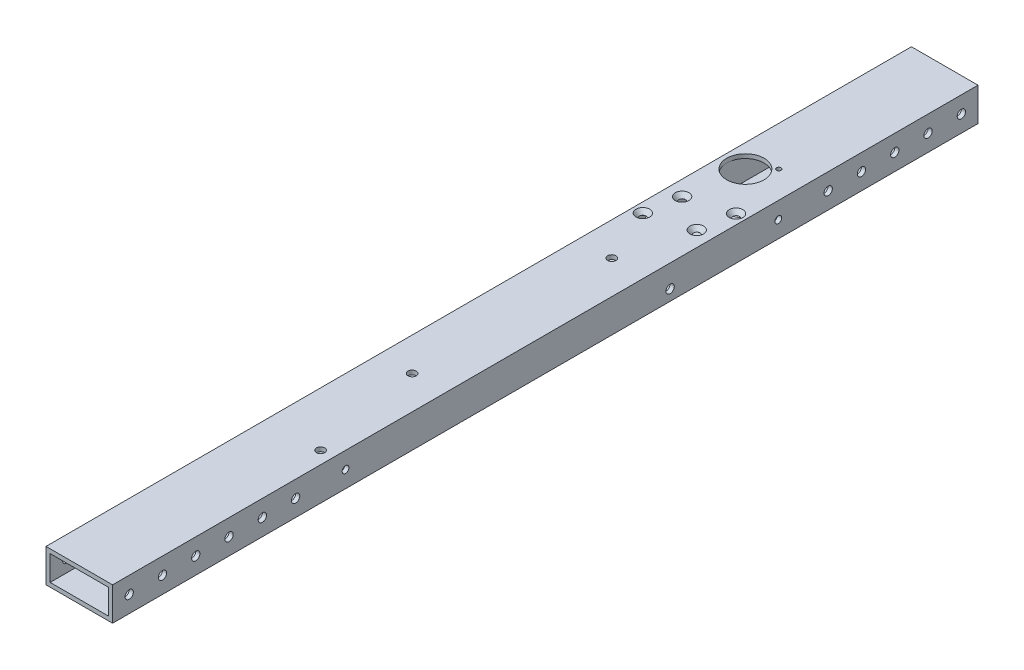
SolidWorks part; units mm, degrees
material "6061 Alloy"
ref_plane "Front Plane" through (0, 0, 0) normal (0, 0, 1) x (1, 0, 0)
ref_plane "Top Plane" through (0, 0, 0) normal (0, 1, 0) x (1, 0, 0)
ref_plane "Right Plane" through (0, 0, 0) normal (1, 0, 0) x (0, 0, -1)
sketch "Sketch1" plane through (0, 0, 0) normal (0, 0, 1) x (1, 0, 0)
  line L0 (-22.225, 9.525) -> (22.225, 9.525)
  line L2 (-25.4, 12.7) -> (25.4, 12.7)
  line L3 (-25.4, 12.7) -> (-25.4, -12.7)
  line L4 (-25.4, -12.7) -> (25.4, -12.7)
  line L5 (25.4, 12.7) -> (25.4, -12.7)
  line L10 (22.225, 9.525) -> (22.225, -9.525)
  line L11 (-22.225, -9.525) -> (22.225, -9.525)
  line L12 (-22.225, 9.525) -> (-22.225, -9.525)
  point P12 (0, 12.7)
  point P14 (25.4, 0)
  dimension "Wall Thickness" = 3.175
  dimension "Outside Width" = 50.8
  dimension "Outside Height" = 25.4
  dimension "Inside Height" = 19.05
  dimension "Inside Width" = 44.45
sketch "Sketch2" plane through (0, 0, 0) normal (1, 0, 0) x (0, 0, -1)
  line L0 (330.2, 0) -> (-330.2, 0)
  point P4 (0, 0)
  point P7 (-330.2, 0)
  point P10 (330.2, 0)
  dimension "Length" = 660.4
sketch "Sketch3" plane through (0, 0, 0) normal (0, 0, 1) x (1, 0, 0)
  line L21 (25.4, 12.7) -> (-25.4, 12.7)
  line L22 (25.4, -12.7) -> (25.4, 12.7)
  line L23 (-25.4, -12.7) -> (25.4, -12.7)
  line L24 (-25.4, 12.7) -> (-25.4, -12.7)
  line L25 (25.4, 12.7) -> (-25.4, 12.7)
  line L26 (25.4, -12.7) -> (25.4, 12.7)
  line L27 (-25.4, -12.7) -> (25.4, -12.7)
  line L28 (-25.4, 12.7) -> (-25.4, -12.7)
  line L29 (22.225, 9.525) -> (-22.225, 9.525)
  line L30 (22.225, -9.525) -> (22.225, 9.525)
  line L31 (-22.225, -9.525) -> (22.225, -9.525)
  line L32 (-22.225, 9.525) -> (-22.225, -9.525)
  line L33 (22.225, 9.525) -> (-22.225, 9.525)
  line L34 (22.225, -9.525) -> (22.225, 9.525)
  line L35 (-22.225, -9.525) -> (22.225, -9.525)
  line L36 (-22.225, 9.525) -> (-22.225, -9.525)
  dimension "D1" = 0
  dimension "D2" = 0
extrude "Boss-Extrude1" add sketch "Sketch3" along normal up to vertex (330.2 mm away) and the other way up to vertex (330.2 mm away) up to point (0, 0, 330.2) other way up to point (0, 0, -330.2)
sketch "Drawing Reference" plane through (0, 0, 0) normal (1, 0, 0) x (0, 0, -1)
  line L0 (-330.2, 0) -> (330.2, 0) construction
  line L1 (0, -12.7) -> (0, 12.7) construction
  line L2 (-330.2, -12.7) -> (330.2, -12.7) construction
  line L5 (-330.2, 12.7) -> (330.2, 12.7) construction
  point P7 (-293.624, 0)
  point P8 (293.624, 0)
  dimension "D1" = 36.576
sketch "Sketch5" plane through (25.4, 0, 0) normal (1, 0, 0) x (0, 0, -1)
  line L2 (-266.7, 0) -> (-241.3, 0)
  line L3 (-241.3, 0) -> (-215.9, 0)
  line L4 (-215.9, 0) -> (-190.5, 0)
  line L5 (-317.5, 0) -> (-330.2, 0)
  line L6 (-330.2, -12.7) -> (-330.2, 12.7) construction
  line L7 (-317.5, 0) -> (-292.1, 0)
  line L8 (-292.1, 0) -> (-266.7, 0)
sketch "Sketch8" plane through (25.4, 0, 0) normal (1, 0, 0) x (0, 0, -1)
  line L0 (330.2, 0) -> (292.1, 0)
  line L1 (330.2, -12.7) -> (330.2, 12.7) construction
  line L2 (292.1, 0) -> (266.7, 0)
  line L3 (266.7, 0) -> (241.3, 0)
  line L4 (241.3, 0) -> (215.9, 0)
  line L5 (330.2, 0) -> (317.5, 0)
hole_wizard "1/4 (0.25) Diameter Hole3" positions "Sketch12" profile "Sketch13" hole size "1/4" standard "ANSI Inch" end condition through all
sketch "Sketch12" plane through (-25.4, 0, 0) normal (-1, 0, 0) x (0, 0, 1)
  point P4 (-317.5, 0)
sketch "Sketch13" plane through (-25.4, 0, -317.5) normal (0, 1, 0) x (0, 0, 1)
  line L0 (0, 0) -> (0, 50.8)
  line L1 (0, 50.8) -> (3.175, 50.8)
  line L2 (3.175, 50.8) -> (3.175, 0)
  line L5 (3.175, 0) -> (0, 0)
  line L11 (0, -6.35) -> (0, 107.95) construction
  dimension "Thru Hole Dia." = 6.35
  dimension "Thru Hole Depth" = 50.8
hole_wizard "1/4 (0.25) Diameter Hole4" positions "Sketch14" profile "Sketch15" hole size "1/4" standard "ANSI Inch" end condition through all
sketch "Sketch14" plane through (-25.4, 0, 0) normal (-1, 0, 0) x (0, 0, 1)
  point P0 (292.1, 0)
  point P3 (317.5, 0)
sketch "Sketch15" plane through (-25.4, 0, 292.1) normal (0, 1, 0) x (0, 0, 1)
  line L0 (0, 0) -> (0, 50.8)
  line L1 (0, 50.8) -> (3.175, 50.8)
  line L2 (3.175, 50.8) -> (3.175, 0)
  line L5 (3.175, 0) -> (0, 0)
  line L11 (0, -6.35) -> (0, 107.95) construction
  dimension "Thru Hole Dia." = 6.35
  dimension "Thru Hole Depth" = 50.8
hole_wizard "1/4 (0.25) Diameter Hole5" positions "Sketch17" profile "Sketch18" hole size "1/4" standard "ANSI Inch" end condition through all
sketch "Sketch17" plane through (25.4, 0, 0) normal (1, 0, 0) x (0, 0, -1)
  point P0 (292.1, 0)
  point P3 (266.7, 0)
sketch "Sketch18" plane through (25.4, 0, -292.1) normal (0, 1, 0) x (0, 0, -1)
  line L0 (0, 0) -> (0, 50.8)
  line L1 (0, 50.8) -> (3.175, 50.8)
  line L2 (3.175, 50.8) -> (3.175, 0)
  line L5 (3.175, 0) -> (0, 0)
  line L11 (0, -6.35) -> (0, 107.95) construction
  dimension "Thru Hole Dia." = 6.35
  dimension "Thru Hole Depth" = 50.8
hole_wizard "1/4 (0.25) Diameter Hole6" positions "Sketch19" profile "Sketch20" hole size "1/4" standard "ANSI Inch" end condition through all
sketch "Sketch19" plane through (25.4, 0, 0) normal (1, 0, 0) x (0, 0, -1)
  point P0 (215.9, 0)
  point P3 (241.3, 0)
sketch "Sketch20" plane through (25.4, 0, -215.9) normal (0, 1, 0) x (0, 0, -1)
  line L0 (0, 0) -> (0, 50.8)
  line L1 (0, 50.8) -> (3.175, 50.8)
  line L2 (3.175, 50.8) -> (3.175, 0)
  line L5 (3.175, 0) -> (0, 0)
  line L11 (0, -6.35) -> (0, 107.95) construction
  dimension "Thru Hole Dia." = 6.35
  dimension "Thru Hole Depth" = 50.8
hole_wizard "1/4 (0.25) Diameter Hole7" positions "Sketch21" profile "Sketch22" hole size "1/4" standard "ANSI Inch" end condition through all
sketch "Sketch21" plane through (25.4, 0, 0) normal (1, 0, 0) x (0, 0, -1)
  point P0 (-190.5, 0)
  point P3 (-215.9, 0)
sketch "Sketch22" plane through (25.4, 0, 190.5) normal (0, 1, 0) x (0, 0, -1)
  line L0 (0, 0) -> (0, 50.8)
  line L1 (0, 50.8) -> (3.175, 50.8)
  line L2 (3.175, 50.8) -> (3.175, 0)
  line L5 (3.175, 0) -> (0, 0)
  line L11 (0, -6.35) -> (0, 107.95) construction
  dimension "Thru Hole Dia." = 6.35
  dimension "Thru Hole Depth" = 50.8
hole_wizard "1/4 (0.25) Diameter Hole8" positions "Sketch23" profile "Sketch24" hole size "1/4" standard "ANSI Inch" end condition through all
sketch "Sketch23" plane through (25.4, 0, 0) normal (1, 0, 0) x (0, 0, -1)
  point P0 (-266.7, 0)
  point P3 (-241.3, 0)
sketch "Sketch24" plane through (25.4, 0, 266.7) normal (0, 1, 0) x (0, 0, -1)
  line L0 (0, 0) -> (0, 50.8)
  line L1 (0, 50.8) -> (3.175, 50.8)
  line L2 (3.175, 50.8) -> (3.175, 0)
  line L5 (3.175, 0) -> (0, 0)
  line L11 (0, -6.35) -> (0, 107.95) construction
  dimension "Thru Hole Dia." = 6.35
  dimension "Thru Hole Depth" = 50.8
sketch "Sketch25" plane through (25.4, 0, 0) normal (1, 0, 0) x (0, 0, -1)
  line L0 (-190.5, 0) -> (-152.4, 0)
  line L1 (215.9, 0) -> (177.8, 0)
hole_wizard "13/64 (0.20313) Diameter Hole1" positions "Sketch26" profile "Sketch27" hole size "13/64" standard "ANSI Inch" end condition through all
sketch "Sketch26" plane through (25.4, 0, 0) normal (1, 0, 0) x (0, 0, -1)
  point P0 (-152.4, 0)
  point P3 (177.8, 0)
sketch "Sketch27" plane through (25.4, 0, 152.4) normal (0, 1, 0) x (0, 0, -1)
  line L0 (0, 0) -> (0, 50.8)
  line L1 (0, 50.8) -> (2.5798, 50.8)
  line L2 (2.5798, 50.8) -> (2.5798, 0)
  line L5 (2.5798, 0) -> (0, 0)
  line L11 (0, -6.35) -> (0, 107.95) construction
  dimension "Thru Hole Dia." = 5.1595
  dimension "Thru Hole Depth" = 50.8
sketch "Sketch28" plane through (-25.4, 0, 0) normal (-1, 0, 0) x (0, 0, 1)
  line L0 (103.1875, 0) -> (77.7875, 0)
  line L1 (-103.1875, 0) -> (-128.5875, 0)
hole_wizard "1/2 (0.5) Diameter Hole1" positions "Sketch29" profile "Sketch30" hole size "1/2" standard "ANSI Inch"
sketch "Sketch29" plane through (-25.4, 0, 0) normal (-1, 0, 0) x (0, 0, 1)
  point P1 (-591.3016, -480.8022)
  point P3 (-103.1875, 0)
  point P6 (77.7875, 0)
  point P9 (103.1875, 0)
  point P13 (-128.5875, 0)
sketch "Sketch30" plane through (-25.4, -480.8022, -591.3016) normal (0, 1, 0) x (0, 0, 1)
  line L0 (0, 0) -> (0, 10.1655)
  line L1 (0, 10.1655) -> (6.35, 6.35)
  line L2 (6.35, 6.35) -> (6.35, 0)
  line L5 (6.35, 0) -> (0, 0)
  line L10 (0, 10.1655) -> (-6.35, 6.35) construction
  line L11 (0, -6.35) -> (0, 107.95) construction
  dimension "Hole Dia." = 12.7
  dimension "Hole Depth" = 6.35
  dimension "Drill Angle" = 118
sketch "Sketch35" plane through (0, -12.7, 0) normal (0, -1, 0) x (1, 0, 0)
  line L0 (25.4, -169.4217) -> (-25.4, -154.3741) construction
  line L1 (-25.4, -154.3741) -> (575.1111, -332.2536) construction
  line L2 (25.4, 330.2) -> (25.4, -330.2) construction
  line L3 (-25.4, -154.3741) -> (-25.4, -205.571) construction
  line L4 (-7.9375, -186.0376) -> (4.8145, -198.7896) construction
  line L5 (-25.4, 330.2) -> (-25.4, -330.2) construction
  line L6 (-22.225, -154.3741) -> (-22.225, -205.571) construction
  line L10 (22.3239, -180.1003) -> (-28.5561, -165.029) construction
  line L11 (22.2439, -180.0766) -> (-28.5561, -165.029) construction
  circle A1 centre (-7.9375, -186.0376) radius 14.2875
  dimension "D1" = 3.175
  dimension "D2" = 11.1125
sketch "Sketch32" plane through (0, -12.7, 0) normal (0, -1, 0) x (1, 0, 0)
  line L1 (17.931, -153.0367) -> (13.819, -127.1821) construction
  line L2 (-13.819, -143.6319) -> (17.931, -153.0367) construction
  line L3 (-17.931, -117.7773) -> (13.819, -127.1821) construction
  line L4 (-13.819, -143.6319) -> (-17.931, -117.7773) construction
hole_wizard "#10 Clearance Hole1" positions "Sketch33" profile "Sketch34" hole size "#10" standard "ANSI Inch" end condition through all
sketch "Sketch33" plane through (0, -12.7, 0) normal (0, -1, 0) x (-1, 0, 0)
  point P0 (13.819, 143.6319)
  point P3 (17.931, 117.7773)
  point P6 (-13.819, 127.1821)
  point P9 (-17.931, 153.0367)
sketch "Sketch34" plane through (-13.819, -12.7, -143.6319) normal (1, 0, 0) x (0, 0, -1)
  line L0 (0, 0) -> (0, 25.4)
  line L1 (0, 25.4) -> (5.2197, 25.4)
  line L2 (2.4892, 22.2589) -> (2.4892, 0)
  line L5 (2.4892, 0) -> (0, 0)
  line L7 (5.2197, 25.4) -> (2.4892, 22.2589)
  line L8 (-5.2197, 25.4) -> (-2.4892, 22.2589) construction
  line L11 (0, -6.35) -> (0, 107.95) construction
  dimension "Thru Hole Dia." = 4.9784
  dimension "Thru Hole Depth" = 25.4
  dimension "Far C'Sink Dia." = 10.4394
  dimension "Far C'Sink Angle" = 82
extrude "Cut-Extrude1" cut sketch "Sketch35" against normal through all
hole_wizard "Tap Drill for #8-32 Tap1" positions "Sketch36" profile "Sketch37" hole size "#8-32" standard "ANSI Inch" end condition through all
sketch "Sketch36" plane through (0, -12.7, 0) normal (0, -1, 0) x (-1, 0, 0)
  point P0 (-4.8145, 198.7896)
sketch "Sketch37" plane through (4.8145, -12.7, -198.7896) normal (1, 0, 0) x (0, 0, -1)
  line L0 (0, 0) -> (0, 25.4)
  line L1 (0, 25.4) -> (1.7272, 25.4)
  line L2 (1.7272, 25.4) -> (1.7272, 0)
  line L5 (1.7272, 0) -> (0, 0)
  line L11 (0, -6.35) -> (0, 107.95) construction
  dimension "Thru Hole Dia." = 3.4544
  dimension "Thru Hole Depth" = 25.4
sketch "Sketch39" plane through (0, -12.7, 0) normal (0, -1, 0) x (1, 0, 0)
  line L0 (25.4, 152.4) -> (0, 152.4) construction
  line L1 (25.4, 190.5) -> (25.4, 152.4) construction
  line L2 (25.4, 330.2) -> (25.4, -330.2) construction
  line L3 (0, 152.4) -> (0, 161.925) construction
  line L4 (0, 152.4) -> (0, 76.2) construction
  line L5 (0, 76.2) -> (0, -76.2) construction
  line L6 (0, 161.925) -> (15.875, 161.925) construction
  dimension "D1" = 76.2
  dimension "D2" = 152.4
  dimension "D3" = 25.4
  dimension "D4" = 9.525
hole_wizard "1/4 (0.25) Diameter Hole9" positions "Sketch40" profile "Sketch41" hole size "1/4" standard "ANSI Inch" end condition through all
sketch "Sketch40" plane through (0, -12.7, 0) normal (0, -1, 0) x (-1, 0, 0)
  point P0 (-15.875, -161.925)
  point P13 (0, -76.2)
  point P17 (0, 76.2)
sketch "Sketch41" plane through (15.875, -12.7, 161.925) normal (1, 0, 0) x (0, 0, -1)
  line L0 (0, 0) -> (0, 25.4)
  line L1 (0, 25.4) -> (3.175, 25.4)
  line L2 (3.175, 25.4) -> (3.175, 0)
  line L5 (3.175, 0) -> (0, 0)
  line L11 (0, -6.35) -> (0, 107.95) construction
  dimension "Thru Hole Dia." = 6.35
  dimension "Thru Hole Depth" = 25.4
sketch "Sketch42" plane through (25.4, 0, 0) normal (1, 0, 0) x (0, 0, -1)
  line L0 (0, 0) -> (95.25, 0) construction
  line L1 (95.25, 0) -> (95.25, -4.45) construction
  line L2 (-330.2, -12.7) -> (330.2, -12.7) construction
  dimension "D1" = 8.25
  dimension "D2" = 95.25
hole_wizard "1/4 (0.25) Diameter Hole10" positions "Sketch43" profile "Sketch44" hole size "1/4" standard "ANSI Inch"
sketch "Sketch43" plane through (25.4, 0, 0) normal (1, 0, 0) x (0, 0, -1)
  point P0 (95.25, -4.45)
sketch "Sketch44" plane through (25.4, -4.45, -95.25) normal (0, 1, 0) x (0, 0, -1)
  line L0 (0, 0) -> (0, 6.9877)
  line L1 (0, 6.9877) -> (3.175, 5.08)
  line L2 (3.175, 5.08) -> (3.175, 0)
  line L5 (3.175, 0) -> (0, 0)
  line L10 (0, 6.9877) -> (-3.175, 5.08) construction
  line L11 (0, -6.35) -> (0, 107.95) construction
  dimension "Hole Dia." = 6.35
  dimension "Hole Depth" = 5.08
  dimension "Drill Angle" = 118
equation "\"D1@Drawing Reference\"=\"Outside Width@Sketch1\" * 0.72"
